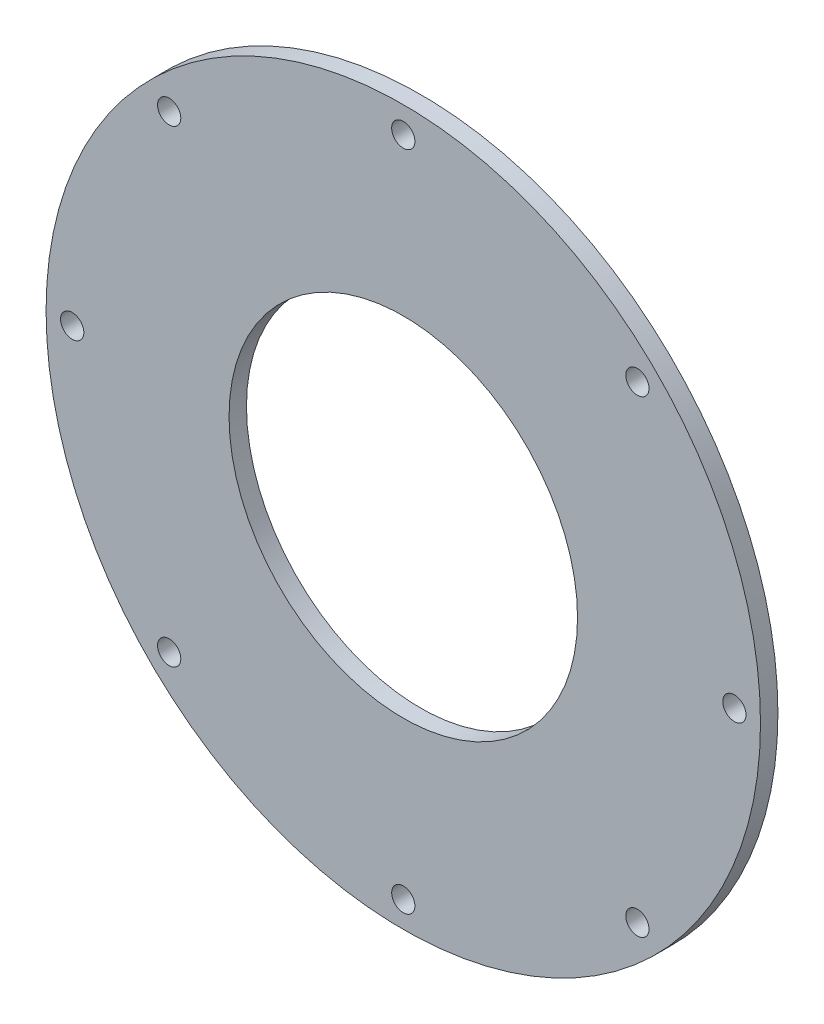
SolidWorks part; units mm, degrees
ref_plane "前视基准面" through (0, 0, 0) normal (0, 0, 1) x (1, 0, 0)
ref_plane "上视基准面" through (0, 0, 0) normal (0, 1, 0) x (1, 0, 0)
ref_plane "右视基准面" through (0, 0, 0) normal (1, 0, 0) x (0, 0, -1)
sketch "草图1" plane through (0, 0, 0) normal (0, 0, 1) x (1, 0, 0)
  line L0 (0, -52.5) -> (0, -61.5) construction
  line L1 (0, 0) -> (36.1973, 0) construction
  line L2 (0, 0) -> (39.2724, -22.6739) construction
  circle A1 centre (0, 0) radius 61.5
  circle A3 centre (0, 0) radius 52.5 construction
  circle A4 centre (0, -57) radius 2
  circle A5 centre (0, -57) radius 3.8 construction
  circle A6 centre (-40.3051, -40.3051) radius 2
  circle A7 centre (-57, 0) radius 2
  circle A8 centre (-40.3051, 40.3051) radius 2
  circle A9 centre (0, 0) radius 23.75 construction
  circle A10 centre (0, 0) radius 22.5 construction
  circle A11 centre (0, -23.75) radius 2.6
  circle A12 centre (-20.5681, 11.875) radius 2.6
  circle A13 centre (20.5681, 11.875) radius 2.6
  circle A14 centre (19.4856, -11.25) radius 2.6
  circle A15 centre (-19.4856, -11.25) radius 2.6
  circle A16 centre (0, 22.5) radius 2.6
  circle A17 centre (0, 0) radius 15.5
  circle A18 centre (0, 57) radius 2
  circle A19 centre (40.3051, 40.3051) radius 2
  circle A20 centre (57, 0) radius 2
  circle A21 centre (40.3051, -40.3051) radius 2
  dimension "D1" = 47.5
  dimension "D2" = 123
  dimension "D3" = 105
  dimension "D4" = 7.6
  dimension "D6" = 45
  dimension "D7" = 5.2
  dimension "D9" = 5.2
  dimension "D10" = 31
  dimension "D8" = 30
  dimension "D5" = 8
extrude "凸台-拉伸1" add sketch "草图1" along normal blind 3
sketch "草图2" plane through (0, 0, 3) normal (0, 0, 1) x (1, 0, 0)
  circle A0 centre (0, 0) radius 30
  dimension "D1" = 60
extrude "切除-拉伸1" cut sketch "草图2" against normal blind 10
